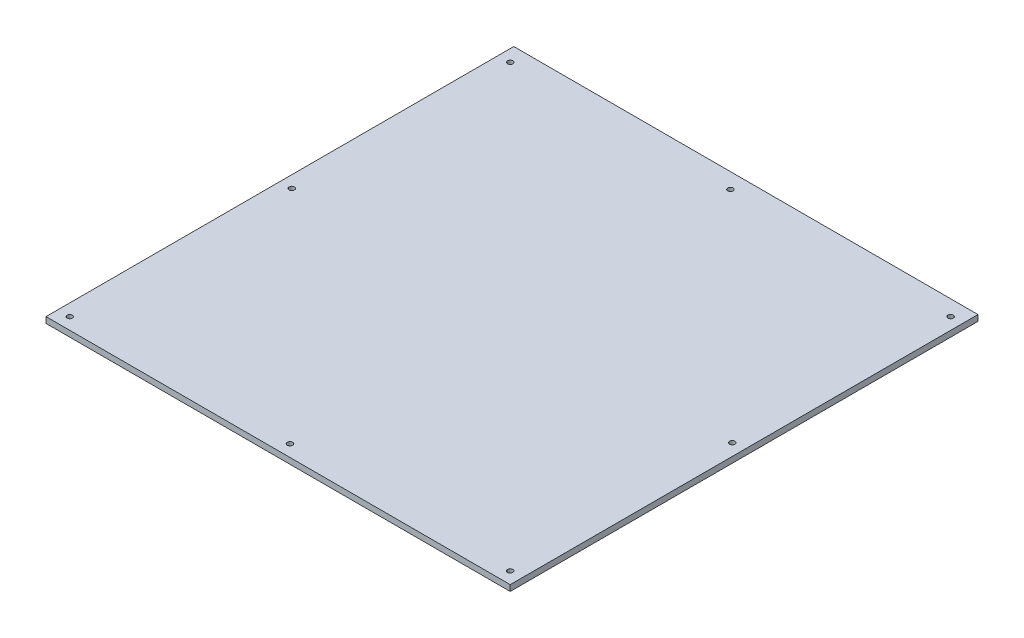
SolidWorks part; units mm, degrees
ref_plane "前基準面" through (0, 0, 0) normal (0, 0, 1) x (1, 0, 0)
ref_plane "上基準面" through (0, 0, 0) normal (0, 1, 0) x (1, 0, 0)
ref_plane "右基準面" through (0, 0, 0) normal (1, 0, 0) x (0, 0, -1)
sketch "草圖1" plane through (0, 0, 0) normal (0, 1, 0) x (1, 0, 0)
  line L1 (-195.5, 197) -> (195.5, 197)
  line L2 (-195.5, 197) -> (-195.5, -197)
  line L3 (-195.5, -197) -> (195.5, -197)
  line L4 (195.5, 197) -> (195.5, -197)
  line L5 (-195.5, 197) -> (195.5, -197) construction
  line L6 (-195.5, -197) -> (195.5, 197) construction
  point P0 (0, 0)
  dimension "D1" = 394
  dimension "D2" = 391
extrude "填料-伸長1" add sketch "草圖1" along normal blind 5
sketch "草圖2" plane through (0, 5, 0) normal (0, 1, 0) x (1, 0, 0)
  line L0 (195.5, 197) -> (-195.5, 197) construction
  line L1 (-195.5, 197) -> (-195.5, -197) construction
  line L2 (195.5, -197) -> (195.5, 197) construction
  line L3 (-2.75, 0) -> (2.75, 0) construction
  line L4 (0, -2.75) -> (0, 2.75) construction
  line L5 (-195.5, -197) -> (195.5, -197) construction
  circle A0 centre (-185.5, 184) radius 2.25
  circle A1 centre (185.5, 184) radius 2.25
  circle A2 centre (-185.5, -187) radius 2.25
  circle A3 centre (185.5, -187) radius 2.25
  circle A4 centre (185.5, 0) radius 2.25
  circle A5 centre (-185.5, 0) radius 2.25
  circle A6 centre (0, 184) radius 2.25
  circle A7 centre (0, -187) radius 2.25
  dimension "D1" = 4.5
  dimension "D2" = 4.5
  dimension "D7" = 4.5
  dimension "D8" = 4.5
  dimension "D9" = 4.5
  dimension "D10" = 4.5
  dimension "D11" = 4.5
  dimension "D19" = 4.5
  dimension "D3" = 13
  dimension "D4" = 10
  dimension "D5" = 13
  dimension "D6" = 10
  dimension "D12" = 13
  dimension "D13" = 10
  dimension "D14" = 10
  dimension "D15" = 10
  dimension "D16" = 10
  dimension "D17" = 10
  dimension "D18" = 10
  dimension "D20" = 10
extrude "除料-伸長1" cut sketch "草圖2" against normal through all
